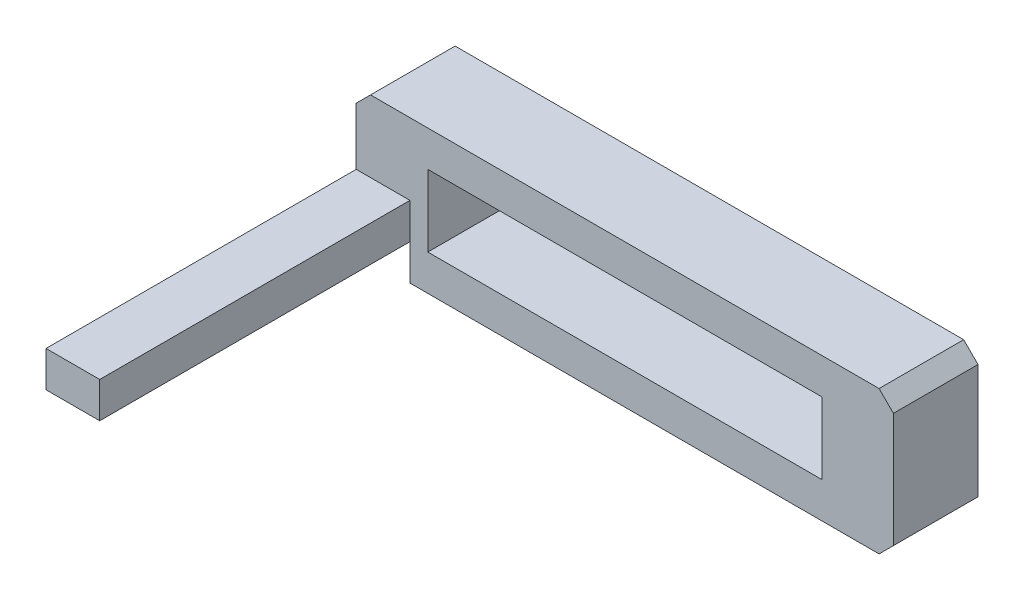
SolidWorks part; units mm, degrees
ref_plane "Front Plane" through (0, 0, 0) normal (0, 0, 1) x (1, 0, 0)
ref_plane "Top Plane" through (0, 0, 0) normal (0, 1, 0) x (1, 0, 0)
ref_plane "Right Plane" through (0, 0, 0) normal (1, 0, 0) x (0, 0, -1)
sketch "Sketch1" plane through (0, 0, 0) normal (0, 0, 1) x (1, 0, 0)
  line L1 (0, 0) -> (-95.25, 0)
  line L2 (0, 0) -> (0, 25.4)
  line L3 (0, 25.4) -> (-95.25, 25.4)
  line L4 (-95.25, 0) -> (-95.25, 25.4)
  line L5 (-12.7, 19.05) -> (-82.55, 19.05)
  line L6 (-12.7, 19.05) -> (-12.7, 6.35)
  line L7 (-12.7, 6.35) -> (-82.55, 6.35)
  line L8 (-82.55, 19.05) -> (-82.55, 6.35)
  point P9 (-47.625, 25.4)
  point P10 (-47.625, 6.35)
  point P11 (-12.7, 21.4142)
  dimension "D1" = 95.25
  dimension "D2" = 25.4
  dimension "D3" = 19.05
  dimension "D4" = 12.7
  dimension "D5" = 6.35
extrude "Boss-Extrude1" add sketch "Sketch1" along normal blind 15 contours L8 L3 L4 L1 L2 L6 L7
sketch "Sketch2" plane through (0, 0, 15) normal (0, 0, 1) x (1, 0, 0)
  line L0 (-95.25, 0) -> (-95.25, 25.4) construction
  line L1 (-95.25, 6.35) -> (-85.725, 6.35)
  line L2 (-95.25, 6.35) -> (-95.25, 12.7)
  line L3 (-95.25, 12.7) -> (-85.725, 12.7)
  line L4 (-85.725, 6.35) -> (-85.725, 12.7)
  line L5 (0, 0) -> (-95.25, 0) construction
  dimension "D1" = 9.525
  dimension "D2" = 6.35
  dimension "D3" = 6.35
extrude "Boss-Extrude2" add sketch "Sketch2" along normal blind 55
chamfer "Chamfer1" distance 2.54 angle 45 4 edges at (0, 0, 7.5) (-95.25, 0, 7.5) (0, 25.4, 7.5) (-95.25, 25.4, 7.5)
sketch "Sketch4" plane through (0, 0, 15) normal (0, 0, 1) x (1, 0, 0)
  line L0 (-95.25, 2.54) -> (-95.25, 6.35) construction
  line L1 (-85.725, 6.35) -> (-95.25, 6.35)
  line L2 (-85.725, 6.35) -> (-85.725, 0)
  line L3 (-85.725, 0) -> (-95.25, 0)
  line L4 (-95.25, 6.35) -> (-95.25, 0)
  line L5 (-2.54, 0) -> (-92.71, 0) construction
extrude "Cut-Extrude2" cut sketch "Sketch4" against normal through all
